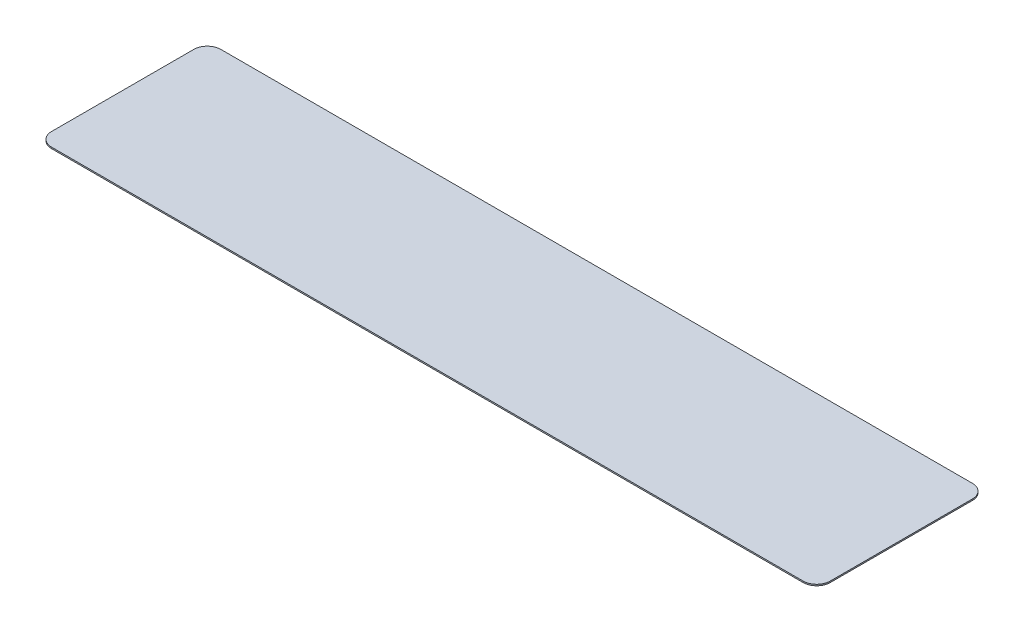
SolidWorks part; units mm, degrees
material "AISI 304 spring"
ref_plane "Front Plane" through (0, 0, 0) normal (0, 0, 1) x (1, 0, 0)
ref_plane "Top Plane" through (0, 0, 0) normal (0, 1, 0) x (1, 0, 0)
ref_plane "Right Plane" through (0, 0, 0) normal (1, 0, 0) x (0, 0, -1)
sketch "Sketch2" plane through (0, 0, 0) normal (0, 1, 0) x (1, 0, 0)
  line L1 (-147.5, -3.3243) -> (74.5, -3.3243)
  line L2 (-151.5, 0.6757) -> (-151.5, 42.6757)
  line L3 (-147.5, 46.6757) -> (74.5, 46.6757)
  line L4 (78.5, 0.6757) -> (78.5, 42.6757)
  line L5 (-151.5, -3.3243) -> (78.5, 46.6757) construction
  line L6 (-151.5, 46.6757) -> (78.5, -3.3243) construction
  arc A0 (-151.5, 42.6757) -> (-147.5, 46.6757) centre (-147.5, 42.6757) cw
  arc A1 (-147.5, -3.3243) -> (-151.5, 0.6757) centre (-147.5, 0.6757) cw
  arc A2 (74.5, -3.3243) -> (78.5, 0.6757) centre (74.5, 0.6757) ccw
  arc A3 (78.5, 42.6757) -> (74.5, 46.6757) centre (74.5, 42.6757) ccw
  point P0 (-36.5, 21.6757)
  dimension "D3" = 4
  dimension "D1" = 230
  dimension "D2" = 50
extrude "Boss-Extrude1" add sketch "Sketch2" along normal blind 0.4 contours L2 A0 L3 A3 L4 A2 L1 A1
